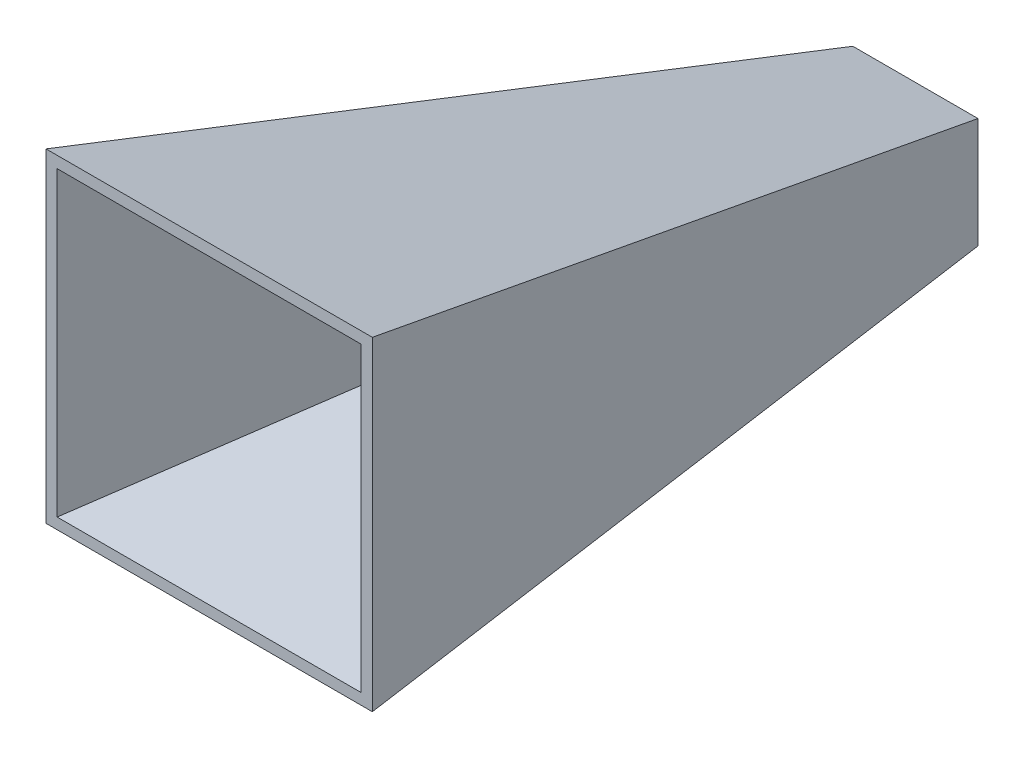
SolidWorks part; units mm, degrees
ref_plane "Front Plane" through (0, 0, 0) normal (0, 0, 1) x (1, 0, 0)
ref_plane "Top Plane" through (0, 0, 0) normal (0, 1, 0) x (1, 0, 0)
ref_plane "Right Plane" through (0, 0, 0) normal (1, 0, 0) x (0, 0, -1)
sketch "Sketch1" plane through (0, 0, 0) normal (0, 0, 1) x (1, 0, 0)
  line L1 (0, 0) -> (140.843, 0)
  line L2 (0, 0) -> (0, 139.954)
  line L3 (0, 139.954) -> (140.843, 139.954)
  line L4 (140.843, 0) -> (140.843, 139.954)
  dimension "D1" = 140.843
  dimension "D2" = 139.954
extrude "Boss-Extrude1" add sketch "Sketch1" along normal blind 304.8
sketch "Sketch2" plane through (140.843, 0, 0) normal (1, 0, 0) x (0, 0, -1)
  line L0 (-304.8, 139.954) -> (0, 47.625)
  line L1 (0, 0) -> (0, 139.954) construction
  line L2 (-304.8, 0) -> (0, 0) construction
  line L3 (-304.8, 139.954) -> (0, 139.954)
  line L4 (0, 139.954) -> (0, 47.625)
  dimension "D1" = 47.625
extrude "Cut-Extrude1" cut sketch "Sketch2" against normal through all
sketch "Sketch3" plane through (0, 0, 0) normal (0, -1, 0) x (1, 0, 0)
  line L0 (70.4215, 304.8) -> (70.4215, 0) construction
  line L1 (0, 304.8) -> (140.843, 304.8) construction
  line L2 (0, 0) -> (140.843, 0) construction
  line L3 (140.843, 304.8) -> (97.4344, 0)
  line L4 (0, 304.8) -> (43.4086, 0)
  line L5 (140.843, 304.8) -> (140.843, 0)
  line L6 (140.843, 0) -> (97.4344, 0)
  line L7 (43.4086, 0) -> (0, 0)
  line L8 (0, 0) -> (0, 304.8)
  dimension "D1" = 27.0129
  dimension "D2" = 27.0129
extrude "Cut-Extrude2" cut sketch "Sketch3" against normal through all
shell "Shell1" thickness 4.7625
equation "\"D2@Sketch3\"=\"D1@Sketch3\""
